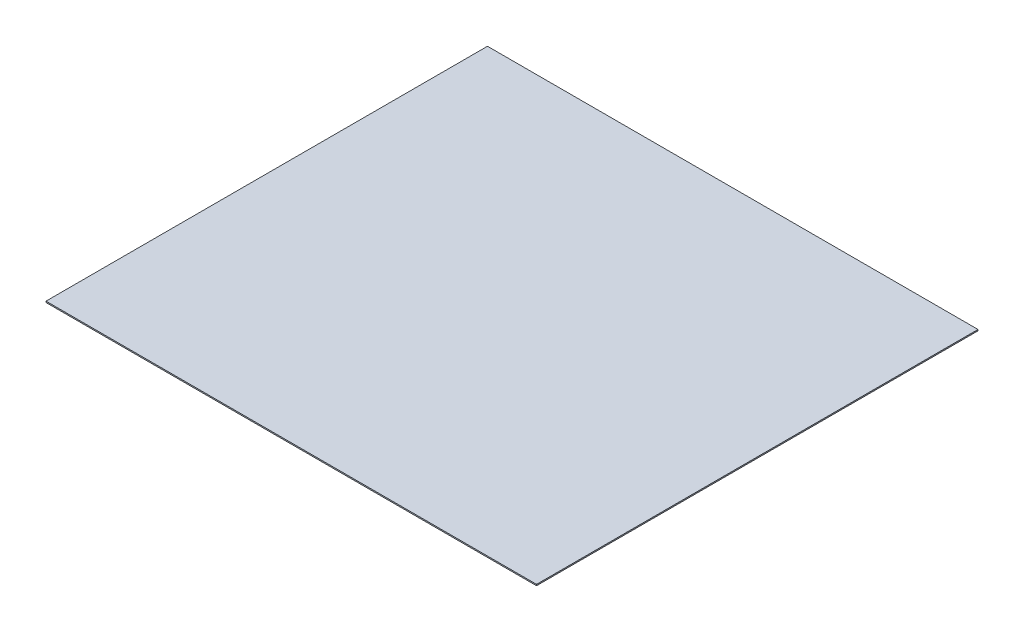
SolidWorks part; units mm, degrees
ref_plane "Front Plane" through (0, 0, 0) normal (0, 0, 1) x (1, 0, 0)
ref_plane "Top Plane" through (0, 0, 0) normal (0, 1, 0) x (1, 0, 0)
ref_plane "Right Plane" through (0, 0, 0) normal (1, 0, 0) x (0, 0, -1)
sketch "Sketch1" plane through (0, 0, 0) normal (0, 1, 0) x (1, 0, 0)
  line L0 (0, 160) -> (0, 0) construction
  line L1 (-220, 180) -> (180, 180)
  line L2 (-220, 180) -> (-220, -180)
  line L3 (-220, -180) -> (180, -180)
  line L4 (180, 180) -> (180, -180)
  line L5 (-160, 160) -> (160, 160) construction
  line L6 (-160, 160) -> (-160, -160) construction
  line L7 (-160, -160) -> (160, -160) construction
  line L8 (160, 160) -> (160, -160) construction
  line L9 (0, 0) -> (160, 0) construction
  line L10 (0, 0) -> (-160, 0) construction
  line L11 (0, 0) -> (0, -160) construction
  line L12 (-120, 160) -> (-120, -160) construction
  line L13 (-80, 160) -> (-80, -160) construction
  line L14 (-40, 160) -> (-40, -160) construction
  line L15 (0, 160) -> (0, -160) construction
  line L16 (40, 160) -> (40, -160) construction
  line L17 (80, 160) -> (80, -160) construction
  line L18 (120, 160) -> (120, -160) construction
  line L19 (-160, 120) -> (160, 120) construction
  line L20 (-160, 80) -> (160, 80) construction
  line L21 (-160, 40) -> (160, 40) construction
  line L22 (-160, 0) -> (160, 0) construction
  line L23 (-160, -40) -> (160, -40) construction
  line L24 (-160, -80) -> (160, -80) construction
  line L25 (-160, -120) -> (160, -120) construction
  dimension "D1" = 360
  dimension "D2" = 400
  dimension "D3" = 320
  dimension "D4" = 320
  dimension "D5" = 20
  dimension "D6" = 20
  dimension "D7" = 8
  dimension "D8" = 8
extrude "Boss-Extrude1" add sketch "Sketch1" along normal blind 1
sketch "Sketch2" plane through (0, 0, 0) normal (0, -1, 0) x (1, 0, 0)
  line L0 (-160, -160) -> (-160, 160) construction
  line L1 (-150, -170) -> (-130, -170)
  line L2 (-150, -170) -> (-150, 170)
  line L3 (-150, 170) -> (-130, 170)
  line L4 (-130, -170) -> (-130, 170)
  line L5 (-160, -160) -> (160, -160) construction
  line L6 (-160, 160) -> (160, 160) construction
  line L7 (-110, -170) -> (-90, -170)
  line L8 (-110, -170) -> (-110, 170)
  line L9 (-110, 170) -> (-90, 170)
  line L10 (-90, -170) -> (-90, 170)
  line L11 (-70, -170) -> (-50, -170)
  line L12 (-70, -170) -> (-70, 170)
  line L13 (-70, 170) -> (-50, 170)
  line L14 (-50, -170) -> (-50, 170)
  line L15 (-30, -170) -> (-10, -170)
  line L16 (-30, -170) -> (-30, 170)
  line L17 (-30, 170) -> (-10, 170)
  line L18 (-10, -170) -> (-10, 170)
  line L19 (10, -170) -> (30, -170)
  line L20 (10, -170) -> (10, 170)
  line L21 (10, 170) -> (30, 170)
  line L22 (30, -170) -> (30, 170)
  line L23 (50, -170) -> (70, -170)
  line L24 (50, -170) -> (50, 170)
  line L25 (50, 170) -> (70, 170)
  line L26 (70, -170) -> (70, 170)
  line L27 (90, -170) -> (110, -170)
  line L28 (90, -170) -> (90, 170)
  line L29 (90, 170) -> (110, 170)
  line L30 (110, -170) -> (110, 170)
  line L31 (130, -170) -> (150, -170)
  line L32 (130, -170) -> (130, 170)
  line L33 (130, 170) -> (150, 170)
  line L34 (150, -170) -> (150, 170)
  line L35 (-160, -120) -> (160, -120) construction
  line L36 (-170, -150) -> (170, -150)
  line L37 (-170, -150) -> (-170, -130)
  line L38 (-170, -130) -> (170, -130)
  line L39 (170, -150) -> (170, -130)
  line L40 (160, -160) -> (160, 160) construction
  line L41 (-170, -110) -> (-170, -90)
  line L42 (-170, -110) -> (170, -110)
  line L43 (-170, -90) -> (170, -90)
  line L44 (170, -110) -> (170, -90)
  line L45 (-170, -70) -> (-170, -50)
  line L46 (-170, -70) -> (170, -70)
  line L47 (-170, -50) -> (170, -50)
  line L48 (170, -70) -> (170, -50)
  line L49 (-170, -30) -> (-170, -10)
  line L50 (-170, -30) -> (170, -30)
  line L51 (-170, -10) -> (170, -10)
  line L52 (170, -30) -> (170, -10)
  line L53 (-170, 10) -> (-170, 30)
  line L54 (-170, 10) -> (170, 10)
  line L55 (-170, 30) -> (170, 30)
  line L56 (170, 10) -> (170, 30)
  line L57 (-170, 50) -> (-170, 70)
  line L58 (-170, 50) -> (170, 50)
  line L59 (-170, 70) -> (170, 70)
  line L60 (170, 50) -> (170, 70)
  line L61 (-170, 90) -> (-170, 110)
  line L62 (-170, 90) -> (170, 90)
  line L63 (-170, 110) -> (170, 110)
  line L64 (170, 90) -> (170, 110)
  line L65 (-170, 130) -> (-170, 150)
  line L66 (-170, 130) -> (170, 130)
  line L67 (-170, 150) -> (170, 150)
  line L68 (170, 130) -> (170, 150)
  dimension "D1" = 20
  dimension "D2" = 10
  dimension "D3" = 10
  dimension "D4" = 10
  dimension "D6" = 20
  dimension "D7" = 10
  dimension "D8" = 10
  dimension "D9" = 10
  dimension "D5" = 8
  dimension "D10" = 8
sketch "Sketch4" plane through (0, 0, 0) normal (0, 1, 0) x (1, 0, 0)
  line L0 (-170, 130) -> (170, 130) construction
  line L1 (-170, 90) -> (170, 90) construction
  line L2 (30, 22.5) -> (140, 22.5) construction
  line L3 (-170, -130) -> (170, -130) construction
  line L4 (-170, -90) -> (170, -90) construction
  line L5 (85, 22.5) -> (94.9387, 22.5)
  line L6 (85, 22.5) -> (85, 14.1516)
  line L7 (-170, -50) -> (170, -50) construction
  line L8 (-170, -10) -> (170, -10) construction
  line L9 (85, 14.1516) -> (94.9387, 14.1516)
  line L10 (94.9387, 22.5) -> (94.9387, 14.1516)
  line L12 (43.9111, 22.5) -> (56.8727, 22.5)
  line L13 (43.9111, 22.5) -> (43.9111, 14.1516)
  line L14 (43.9111, 14.1516) -> (56.8727, 14.1516)
  line L15 (56.8727, 22.5) -> (56.8727, 14.1516)
  line L16 (24.5436, 24.2342) -> (34.1902, 24.2342)
  line L17 (24.5436, 24.2342) -> (24.5436, 14.1516)
  line L18 (24.5436, 14.1516) -> (34.1902, 14.1516)
  line L19 (-170, 70) -> (170, 70) construction
  line L20 (34.1902, 24.2342) -> (34.1902, 14.1516)
  line L21 (-15.5285, 4.2279) -> (-4.4087, 4.2279)
  line L22 (-15.5285, 4.2279) -> (-15.5285, -6.2112)
  line L23 (-15.5285, -6.2112) -> (-4.4087, -6.2112)
  line L24 (-40, 160) -> (-40, -160) construction
  line L25 (-170, 10) -> (170, 10) construction
  line L26 (-4.4087, 4.2279) -> (-4.4087, -6.2112)
  line L27 (-134.1439, 24.2342) -> (-126.798, 24.2342)
  line L28 (-134.1439, 24.2342) -> (-134.1439, 15.6289)
  line L29 (-134.1439, 15.6289) -> (-126.798, 15.6289)
  line L30 (-126.798, 24.2342) -> (-126.798, 15.6289)
  line L31 (-95.3154, 24.2342) -> (-86.7102, 24.2342)
  line L32 (-95.3154, 24.2342) -> (-95.3154, 13.74)
  line L33 (-95.3154, 13.74) -> (-86.7102, 13.74)
  line L34 (-86.7102, 24.2342) -> (-86.7102, 13.74)
  line L35 (-54.1783, 24.2342) -> (-47.8818, 24.2342)
  line L36 (-54.1783, 24.2342) -> (-54.1783, 13.74)
  line L37 (-54.1783, 13.74) -> (-47.8818, 13.74)
  line L38 (-47.8818, 24.2342) -> (-47.8818, 13.74)
  line L39 (124.8809, 24.2342) -> (134.3985, 24.2342)
  line L40 (124.8809, 24.2342) -> (124.8809, 14.1516)
  line L41 (124.8809, 14.1516) -> (134.3985, 14.1516)
  line L42 (134.3985, 24.2342) -> (134.3985, 14.1516)
  circle A0 centre (-19.8085, 130) radius 3.9178
  circle A1 centre (-19.8085, 90) radius 3.178
  circle A3 centre (-20, -130) radius 2.685
  circle A4 centre (-20, -90) radius 4.1731
  circle A6 centre (-20, -50) radius 3.158
  circle A7 centre (-20, -10) radius 3.6619
  circle A18 centre (-19.8085, 70) radius 4.6301
  circle A23 centre (-40, 10) radius 4.1516
